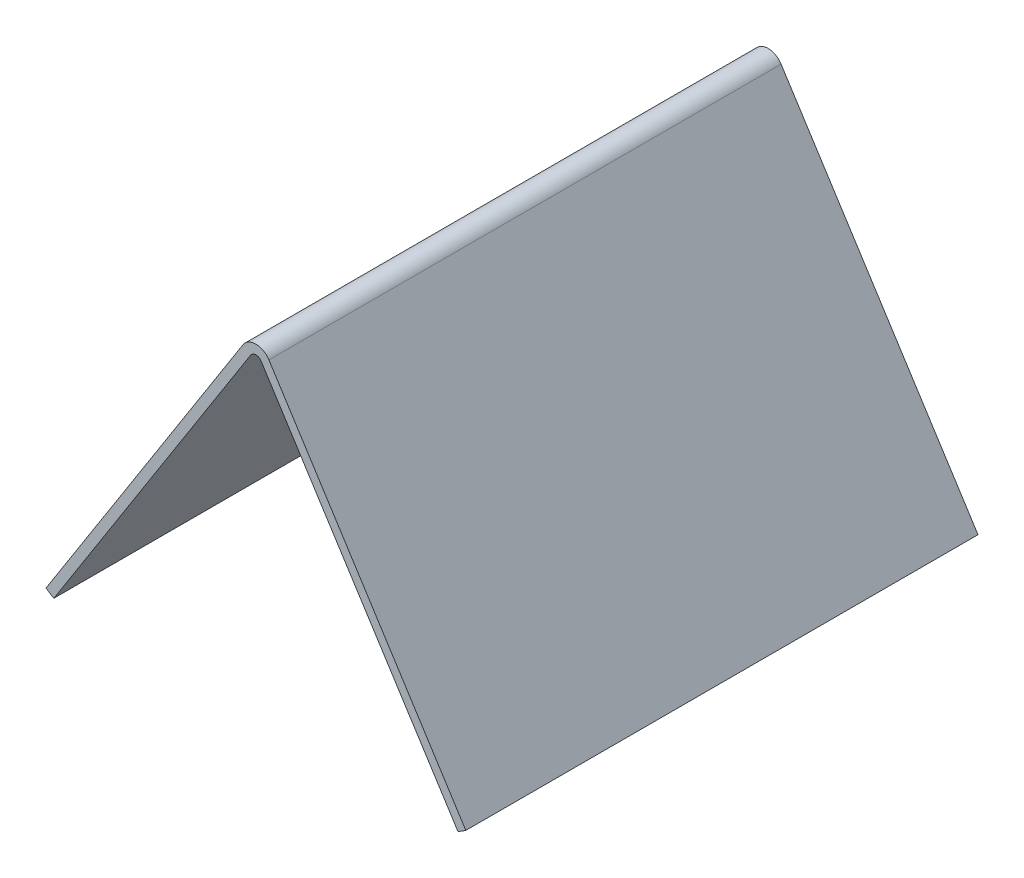
SolidWorks part; units mm, degrees
ref_plane "Front Plane" through (0, 0, 0) normal (0, 0, 1) x (1, 0, 0)
ref_plane "Top Plane" through (0, 0, 0) normal (0, 1, 0) x (1, 0, 0)
ref_plane "Right Plane" through (0, 0, 0) normal (1, 0, 0) x (0, 0, -1)
sketch "Sketch1" plane through (0, 0, 0) normal (0, 0, 1) x (1, 0, 0)
  line L0 (0, 0) -> (0, 145.7232) construction
  line L1 (-70.5, -139) -> (70.5, -139) construction
  line L2 (-70.5, -139) -> (-70.5, 139) construction
  line L3 (-70.5, 139) -> (70.5, 139) construction
  line L4 (70.5, -139) -> (70.5, 139) construction
  line L5 (-70.5, -139) -> (70.5, 139) construction
  line L6 (-70.5, 139) -> (70.5, -139) construction
  line L7 (0, 145.7232) -> (-68, 38.9846) construction
  line L8 (-65.5, 9.4079) -> (-1.6868, 109.5746)
  line L9 (-68.0302, 11.0198) -> (-4.217, 111.1865)
  line L10 (-65.5, 9.4079) -> (-68.0302, 11.0198)
  line L11 (-65.5, 9.4079) -> (-65.5, 8.4079)
  line L12 (-65.5, 8.4079) -> (-70.5, 8.4079)
  line L13 (-70.5, 8.4079) -> (-70.5, 37.3253)
  line L14 (-67.217, 40.2137) -> (-16.8678, 119.246)
  line L15 (-68, 14.5577) -> (-68, 37.5272)
  line L16 (-18.5546, 120.3206) -> (-69.717, 40.0118)
  line L17 (65.5, 9.4079) -> (65.5, 8.4079)
  line L18 (65.5, 9.4079) -> (68.0302, 11.0198)
  line L19 (65.5, 8.4079) -> (70.5, 8.4079)
  line L20 (70.5, 8.4079) -> (70.5, 37.3253)
  line L21 (68, 14.5577) -> (68, 37.5272)
  line L22 (65.5, 9.4079) -> (1.6868, 109.5746)
  line L23 (68.0302, 11.0198) -> (4.217, 111.1865)
  line L24 (67.217, 40.2137) -> (16.8678, 119.246)
  line L25 (18.5546, 120.3206) -> (69.717, 40.0118)
  line L26 (-68.0302, 11.0198) -> (-66.4183, 13.55)
  line L27 (-66.4183, 13.55) -> (-68, 14.5577)
  line L28 (66.4183, 13.55) -> (68, 14.5577)
  line L29 (-65.5, 8.4079) -> (-65.5, 3.4079)
  line L30 (-65.5, 3.4079) -> (-15.1236, -135)
  line L31 (-15.1236, -135) -> (15.1236, -135)
  line L32 (25.5253, -74.8874) -> (65.5, 3.4079)
  line L33 (17.9245, -139) -> (-17.9245, -139)
  line L34 (-17.9245, -139) -> (-70.5, 5.4501)
  line L35 (-70.5, 5.4501) -> (-70.5, 8.4079)
  line L36 (-70.5, 8.4079) -> (-70.5, 5.4501)
  line L37 (65.5, 3.4079) -> (15.1236, -135)
  line L38 (17.9245, -139) -> (70.5, 5.4501)
  line L39 (65.5, 8.4079) -> (70.5, 8.4079)
  line L40 (65.5, 8.4079) -> (65.5, 3.4079)
  line L41 (70.5, 5.4501) -> (70.5, 8.4079)
  line L42 (-25.5253, -74.8874) -> (-65.5, 3.4079)
  arc A0 (-1.6868, 109.5746) -> (1.6868, 109.5746) centre (0, 108.5) cw
  arc A1 (-4.217, 111.1865) -> (4.217, 111.1865) centre (0, 108.5) cw
  arc A2 (-16.8678, 119.246) -> (16.8678, 119.246) centre (0, 108.5) cw
  arc A3 (-69.717, 40.0118) -> (-70.5, 37.3253) centre (-65.5, 37.3253) ccw
  arc A4 (-67.217, 40.2137) -> (-68, 37.5272) centre (-63, 37.5272) ccw
  arc A5 (-18.5546, 120.3206) -> (18.5546, 120.3206) centre (0, 108.5) cw
  arc A6 (67.217, 40.2137) -> (68, 37.5272) centre (63, 37.5272) cw
  arc A7 (69.717, 40.0118) -> (70.5, 37.3253) centre (65.5, 37.3253) cw
  arc A9 (-25.5253, -74.8874) -> (25.5253, -74.8874) centre (0, -61.8551) ccw
  circle A10 centre (-1.6868, -115) radius 11
  point P0 (0, 0)
  point P24 (-70.5, 38.7827)
  dimension "D5" = 2
  dimension "D10" = 5
  dimension "D21" = 22
  dimension "D1" = 141
  dimension "D2" = 278
  dimension "D3" = 32.5
  dimension "D4" = 3
  dimension "D6" = 15
  dimension "D7" = 1
  dimension "D8" = 5
  dimension "D9" = 2
  dimension "D11" = 30.5
  dimension "D12" = 100.1667
  dimension "D13" = 148.4079
  dimension "D14" = 3
  dimension "D15" = 2.5
  dimension "D16" = 5
  dimension "D17" = 4
  dimension "D18" = 4
  dimension "D19" = 70
  dimension "D20" = 20
extrude "Boss-Extrude1" add sketch "Sketch1" along normal blind 166 contours A1 L9 L10 L8 A0 L22 L18 L23
